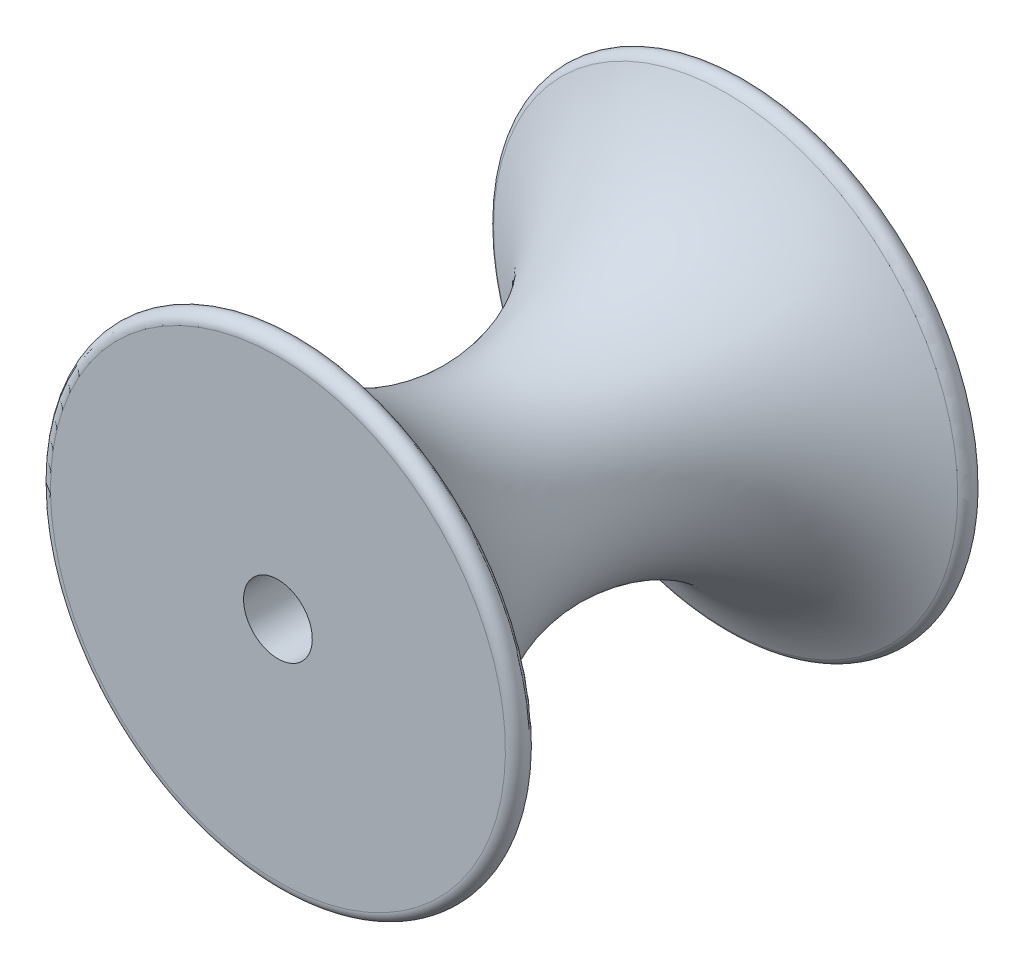
SolidWorks part; units mm, degrees
ref_plane "Front Plane" through (0, 0, 0) normal (0, 0, 1) x (1, 0, 0)
ref_plane "Top Plane" through (0, 0, 0) normal (0, 1, 0) x (1, 0, 0)
ref_plane "Right Plane" through (0, 0, 0) normal (1, 0, 0) x (0, 0, -1)
sketch "Sketch1" plane through (0, 0, 0) normal (1, 0, 0) x (0, 0, -1)
  line L0 (11, 0) -> (-11, 0) construction
  line L2 (11, 1.6) -> (-11, 1.6) construction
  line L4 (0, 11.3535) -> (0, -11.3535) construction
  line L5 (11, 1.6) -> (11, 15.5) construction
  line L6 (-11, 1.6) -> (-11, 15.5) construction
  line L7 (10.9, 1.6) -> (10.9, 14.0201)
  line L8 (-10.9, 1.6) -> (-10.9, 14.0201)
  line L9 (10.9, 1.6) -> (-10.9, 1.6)
  line L10 (11, 0) -> (11, -24.7641) construction
  circle A0 centre (0, 15.5) radius 11 construction
  arc A1 (10.9, 14.0201) -> (-10.9, 14.0201) centre (0, 15.5) cw
  point P2 (0, 0)
  point P5 (0, 0)
  point P21 (0, 0)
  dimension "D1" = 0.2
revolve "Revolve1" add sketch "Sketch1" angle 360 about L0
fillet "Fillet1" radius 0.5 2 edges at (0, 14.0201, 10.9) (0, 14.0201, -10.9)
